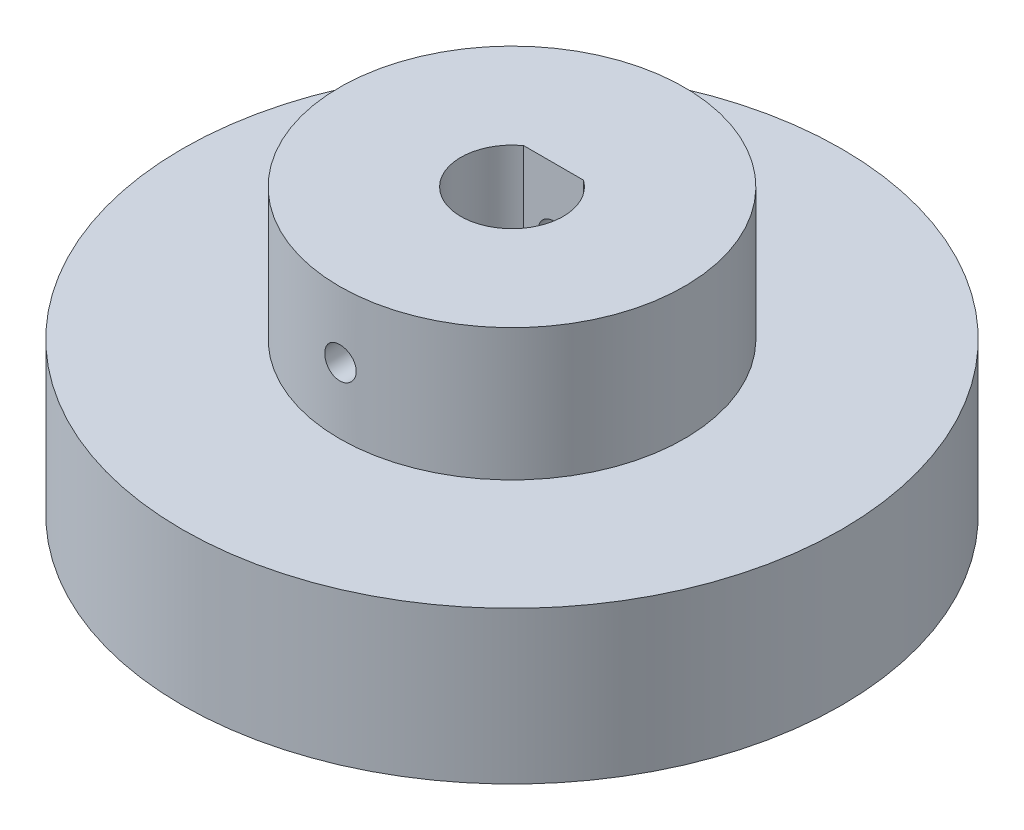
SolidWorks part; units mm, degrees
ref_plane "Front Plane" through (0, 0, 0) normal (0, 0, 1) x (1, 0, 0)
ref_plane "Top Plane" through (0, 0, 0) normal (0, 1, 0) x (1, 0, 0)
ref_plane "Right Plane" through (0, 0, 0) normal (1, 0, 0) x (0, 0, -1)
sketch "Sketch1" plane through (0, 0, 0) normal (0, 1, 0) x (1, 0, 0)
  circle A0 centre (0, 0) radius 32.5
  dimension "D1" = 65
extrude "Boss-Extrude1" add sketch "Sketch1" along normal blind 15
sketch "Sketch2" plane through (0, 15, 0) normal (0, 1, 0) x (1, 0, 0)
  circle A0 centre (0, 0) radius 17
  dimension "D1" = 34
extrude "Boss-Extrude2" add sketch "Sketch2" along normal blind 13
sketch "Sketch3" plane through (0, 0, 0) normal (0, 0, 1) x (1, 0, 0)
  line L0 (-16.9553, 15) -> (17, 28) construction
  line L1 (32.5, 15) -> (-32.5, 15) construction
  line L2 (17, 15) -> (-17, 28) construction
  line L3 (-17, 28) -> (-17, 15) construction
  line L4 (17, 28) -> (-17, 28) construction
  circle A0 centre (0.0224, 21.5) radius 1.55
  dimension "D1" = 3.1
extrude "Cut-Extrude2" cut sketch "Sketch3" against normal through all and the other way through all
sketch "Sketch4" plane through (0, 28, 0) normal (0, 1, 0) x (1, 0, 0)
  line L0 (0, 0) -> (0, 4.1) construction
  line L1 (-2.9483, 4.1) -> (2.9483, 4.1)
  arc A0 (-2.9483, 4.1) -> (2.9483, 4.1) centre (0, 0) ccw
  point P7 (0, 4.1)
  dimension "D1" = 10.1
  dimension "D2" = 4.1
  dimension "D3" = 4.1
extrude "Cut-Extrude3" cut sketch "Sketch4" against normal through all
